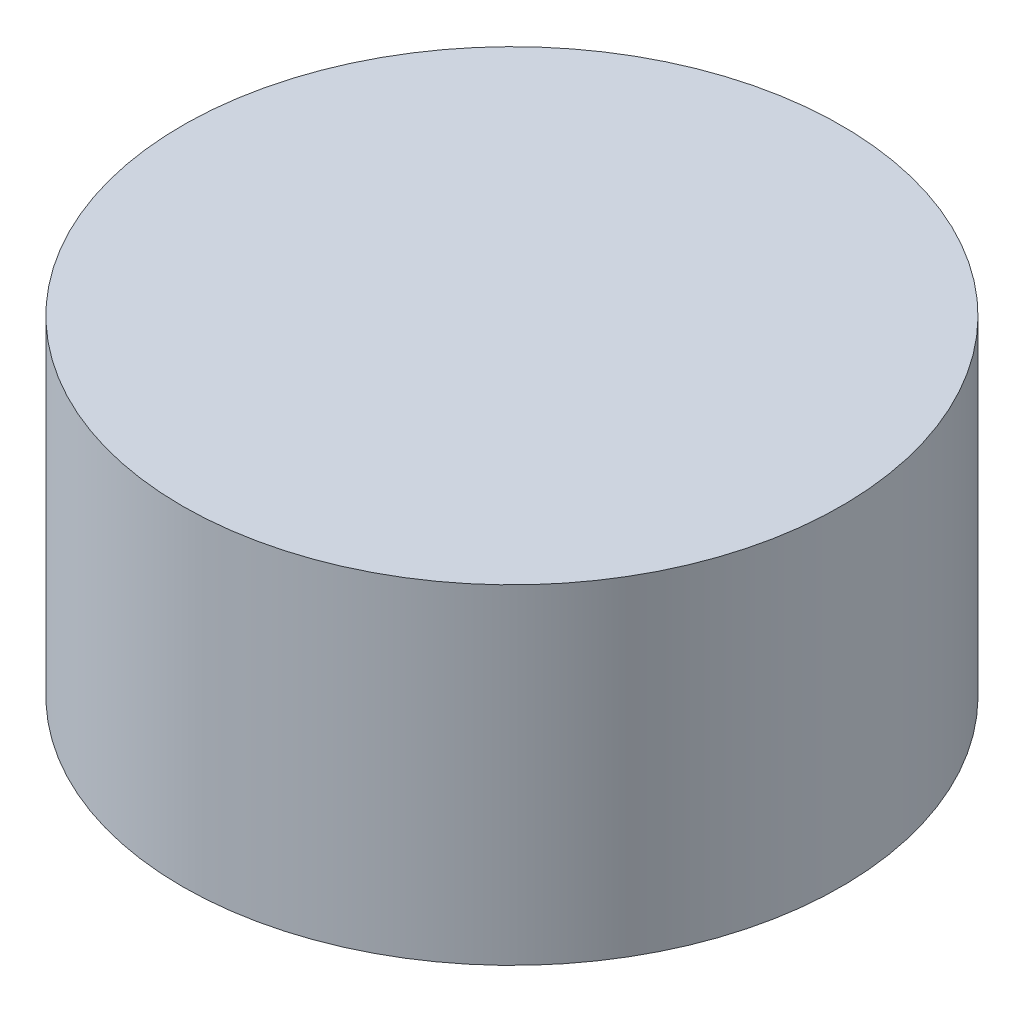
SolidWorks part; units mm, degrees
material "Acier inoxydable chromé"
ref_plane "Plan de face" through (0, 0, 0) normal (0, 0, 1) x (1, 0, 0)
ref_plane "Plan de dessus" through (0, 0, 0) normal (0, 1, 0) x (1, 0, 0)
ref_plane "Plan de droite" through (0, 0, 0) normal (1, 0, 0) x (0, 0, -1)
sketch "base" plane through (0, 0, 0) normal (0, 0, 1) x (1, 0, 0)
  line L0 (0, -1.7345) -> (0, -2.2345)
  line L1 (0, -1.7345) -> (0.5, -1.7345)
  line L2 (0.5, -1.7345) -> (0.5, -2.2345)
  line L3 (0.5, -2.2345) -> (0, -2.2345)
  line L4 (0, 0.7745) -> (0, -2.2345) construction
  dimension "DI" = 0
  dimension "W" = 0.5
  dimension "H" = 0.5
revolve "rev" add sketch "base" angle 360 about L4
equation "\"DI@base\"=\"magnet_levitation_DI\" / 2"
equation "\"W@base\"=( \"magnet_levitation_DE\" - \"magnet_levitation_DI\" )  / 2"
equation "\"H@base\"=\"magnet_levitation_H\""
equation "\"magnet_DI\"= 3mm'inner diameter of the o-ring magnet"
equation "\"magnet_DE\"= 8mm'external diameter of the o-ring magnet"
equation "\"magnet_H\"= 3mm'tall of the magnet"
equation "\"gap_magnet_H\"= 1mm'gap between the 2 magnets"
equation "\"plug_DI\"= 1.5mm'size of the inner extrude of the plug (finger contact)"
equation "\"magnet_levitation_DI\"= 0mm'inner diameter of the o-ring magnet"
equation "\"magnet_levitation_DE\"= 1mm'external diameter of the o-ring magnet"
equation "\"magnet_levitation_H\"= 0.5mm'tall of the magnet"
equation "\"coil_H\"= 8mm 'height coil"
equation "\"coil_W\"= 0.2mm 'width coil"
equation "\"mandrine_freegap\"= 0.2mm 'gap between the magnet and the mandrine. "
equation "\"mandrine_bottom_H\"= 0.5mm 'border of the bottom of the mandrine"
equation "\"mandrine_coilmagnet_wall\"= 0.15mm"
equation "\"mandrine_magnet_lev\"= 3mm' gap needed for the levitation of the rod"
equation "\"mandrine_border_H\"= 2mm 'border of the top of the mandrine"
equation "\"mandrine_epoxy_W\"= 0.5mm 'width epoxy"
equation "\"mandrine_DI\"= \"mandrine_freegap\"*2+\"magnet_DE\""
equation "\"mandrine_DE\"= (\"mandrine_epoxy_W\"+\"coil_W\"+\"mandrine_coilmagnet_wall\")*2+\"mandrine_DI\""
equation "\"mandrine_H\"= \"magnet_levitation_H\"+\"mandrine_magnet_lev\"+\"magnet_H\"+\"gap_magnet_H\"/2+\"coil_H\"/2+\"mandrine_border_H\""
equation "\"apex_tower_freegap\"= 1.25mm 'gap between the actuator and the tower"
equation "\"apex_tower_Dbase\"= 2.5mm 'diameter of the holes in order to curve"
equation "\"apex_tower_Hbase\"= 1mm 'gap between the bottom of the tower and the holes"
equation "\"apex_tower_hole\"= 4.5mm 'witdh of the hole"
equation "\"apex_tower_H\"= 0mm '\"mandrine_H\"-\"tower_link_H\""
equation "\"apex_tower_W\"= 1.5mm 'width of the tower"
equation "\"tower_DI\"= \"mandrine_DE\"+\"tower_freegap\""
equation "\"tower_W\"= 1mm'width of the tower"
equation "\"tower_link_H\"= 2mm"
equation "\"tower_link_W\"= 4mm"
equation "\"actuator1.x\"= 42.59mm"
equation "\"actuator1.z\"= 45.834mm"
equation "\"actuator1.y\"= 101.167mm"
equation "\"actuator2.x\"= 80.026mm"
equation "\"actuator2.z\"= 37.834mm"
equation "\"actuator2.y\"= 120.647mm"
equation "\"actuator3.x\"= 0mm"
equation "\"actuator3.z\"= 13mm"
equation "\"actuator3.y\"= 45.677mm"
equation "\"actuator4.x\"= 14.55mm"
equation "\"actuator4.z\"= 33.9226mm"
equation "\"actuator4.y\"= 66.047mm"
equation "\"actuator5.x\"= 14.557mm"
equation "\"actuator5.z\"= 51.234mm"
equation "\"actuator5.y\"= 45.327mm"
equation "\"actuator6.x\"= 12.497mm"
equation "\"actuator6.z\"= 29.9773mm"
equation "\"actuator6.y\"= 28.807mm"
equation "\"actuator7.x\"= 27.494mm"
equation "\"actuator7.z\"= 49.434mm"
equation "\"actuator7.y\"= 13.807mm"
equation "\"actuator8.x\"= 39.75mm"
equation "\"actuator8.z\"= 31.7209mm"
equation "\"actuator8.y\"= 30.087mm"
equation "\"actuator9.x\"= 41.5767mm"
equation "\"actuator9.z\"= 60.084mm"
equation "\"actuator9.y\"= 49.157mm"
equation "\"actuator10.x\"= 41.148mm"
equation "\"actuator10.z\"= 45.3632mm"
equation "\"actuator10.y\"= 71.787mm"
equation "\"actuator11.x\"= 70.869mm"
equation "\"actuator11.z\"= 42.0948mm"
equation "\"actuator11.y\"= 78.407mm"
equation "\"actuator12.x\"= 77.15mm"
equation "\"actuator12.z\"= 33.6927mm"
equation "\"actuator12.y\"= 52.377mm"
equation "\"actuator13.x\"= 70.87mm"
equation "\"actuator13.z\"= 48.7255mm"
equation "\"actuator13.y\"= 25.793mm"
equation "\"actuator14.x\"= 80.15mm"
equation "\"actuator14.z\"= 45.0141mm"
equation "\"actuator14.y\"= 0.711mm"
equation "\"actuator15.x\"= 92.21mm"
equation "\"actuator15.z\"= 63.034mm"
equation "\"actuator15.y\"= 34.092mm"
equation "\"actuator16.x\"= 97.61mm"
equation "\"actuator16.z\"= 50.5713mm"
equation "\"actuator16.y\"= 57.427mm"
equation "\"actuator17.x\"= 87.41mm"
equation "\"actuator17.z\"= 61.634mm"
equation "\"actuator17.y\"= 86.987mm"
equation "\"actuator18.x\"= 109.08mm"
equation "\"actuator18.z\"= 46.3531mm"
equation "\"actuator18.y\"= 92.077mm"
equation "\"actuator19.x\"= 125.04mm"
equation "\"actuator19.z\"= 57.834mm"
equation "\"actuator19.y\"= 63.187mm"
equation "\"actuator20.x\"= 119.466mm"
equation "\"actuator20.z\"= 58.534mm"
equation "\"actuator20.y\"= 34.434mm"
equation "\"actuator21.x\"= 115.558mm"
equation "\"actuator21.z\"= 44.984mm"
equation "\"actuator21.y\"= 0mm"
equation "\"actuator22.x\"= 142.74mm"
equation "\"actuator22.z\"= 45.5969mm"
equation "\"actuator22.y\"= 38.901mm"
equation "\"actuator23.x\"= 145.93mm"
equation "\"actuator23.z\"= 42.2671mm"
equation "\"actuator23.y\"= 70.278mm"
equation "\"actuator24.x\"= 131.11mm"
equation "\"actuator24.z\"= 33.4578mm"
equation "\"actuator24.y\"= 100.8741mm"
equation "\"shape_freegap\"= \"tower_freegap\""
equation "\"shape_holes_sweat_D\"= 2mm"
equation "\"shape_holes_actuator_D\"= \"magnet_DE\"+\"shape_freegap\"+1mm"
